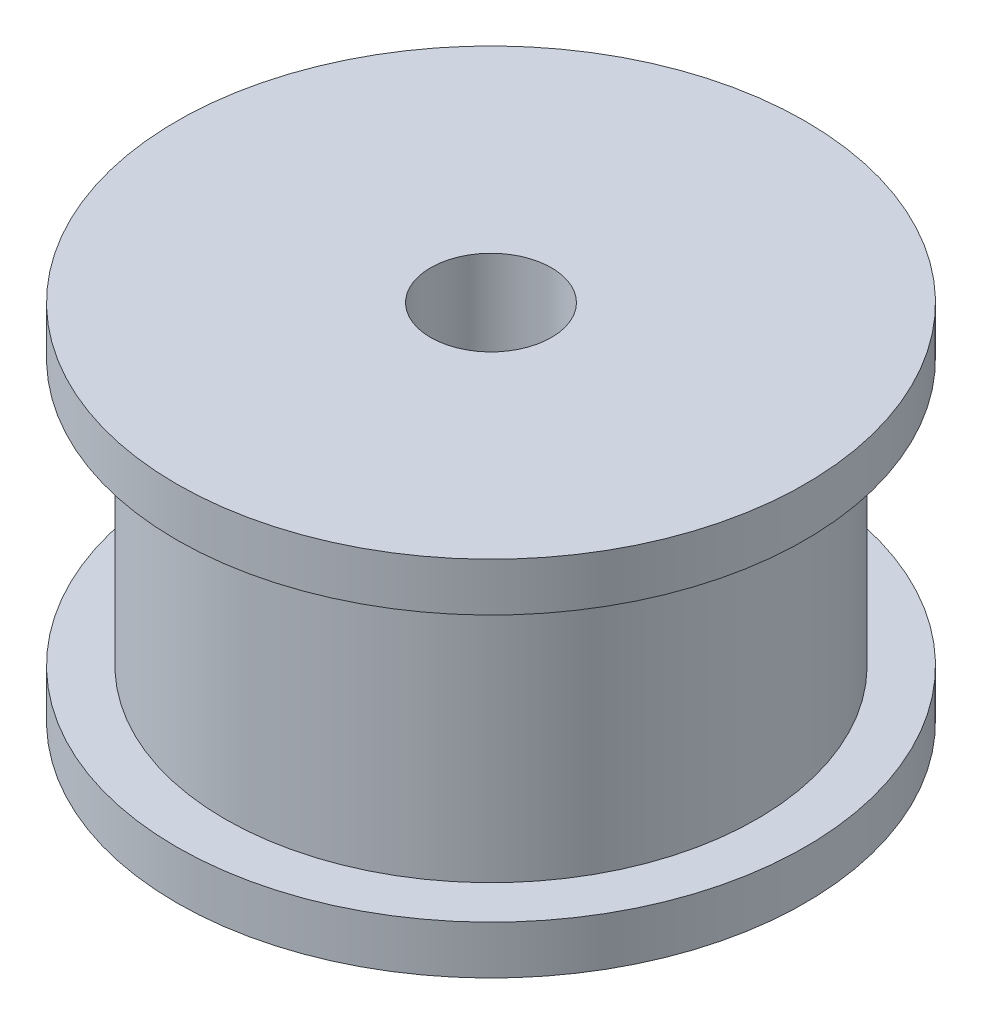
SolidWorks part; units mm, degrees
ref_plane "前视基准面" through (0, 0, 0) normal (0, 0, 1) x (1, 0, 0)
ref_plane "上视基准面" through (0, 0, 0) normal (0, 1, 0) x (1, 0, 0)
ref_plane "右视基准面" through (0, 0, 0) normal (1, 0, 0) x (0, 0, -1)
sketch "草图1" plane through (0, 0, 0) normal (0, 1, 0) x (1, 0, 0)
  circle A0 centre (0, 0) radius 13
  dimension "D1" = 26
extrude "凸台-拉伸1" add sketch "草图1" along normal blind 2
sketch "草图2" plane through (0, 2, 0) normal (0, 1, 0) x (1, 0, 0)
  circle A0 centre (0, 0) radius 11
  dimension "D1" = 22
extrude "凸台-拉伸2" add sketch "草图2" along normal blind 11
sketch "草图3" plane through (0, 13, 0) normal (0, 1, 0) x (1, 0, 0)
  circle A0 centre (0, 0) radius 13
  dimension "D1" = 26
extrude "凸台-拉伸3" add sketch "草图3" along normal blind 2
hole_wizard "孔1" positions "草图4" profile "草图5" legacy end condition up to next
sketch "草图4" plane through (0, 15, 0) normal (0, 1, 0) x (1, 0, 0)
  point P0 (0, 0)
sketch "草图5" plane through (0, 15, 0) normal (1, 0, 0) x (0, 0, 1)
  line L0 (0, 0) -> (0, 15)
  line L1 (0, 15) -> (2.5, 15)
  line L2 (2.5, 15) -> (2.5, 0)
  line L3 (2.5, 0) -> (0, 0)
  line L4 (0, 110) -> (0, -10) construction
  dimension "直径" = 5
  dimension "深度" = 15
